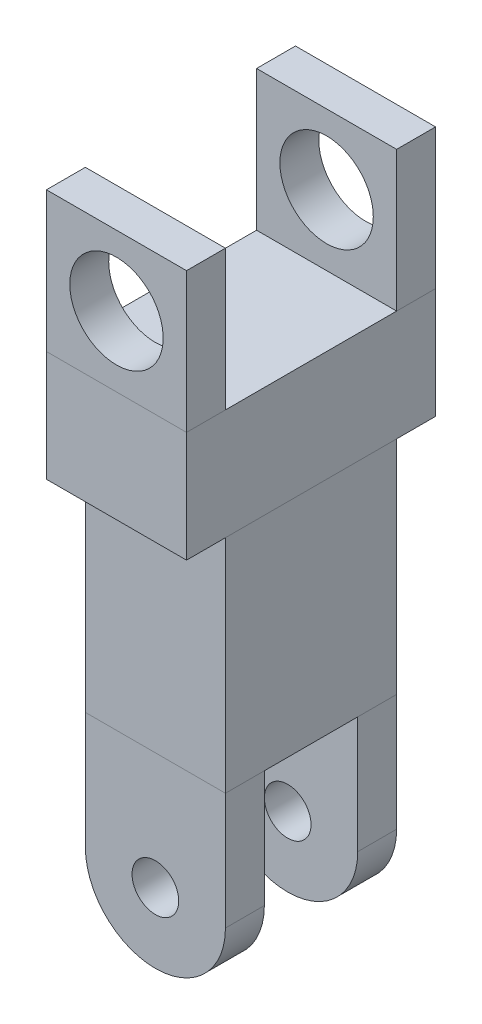
SolidWorks part; units mm, degrees
ref_plane "Front Plane" through (0, 0, 0) normal (0, 0, 1) x (1, 0, 0)
ref_plane "Top Plane" through (0, 0, 0) normal (0, 1, 0) x (1, 0, 0)
ref_plane "Right Plane" through (0, 0, 0) normal (1, 0, 0) x (0, 0, -1)
sketch "Sketch1" plane through (0, 0, 0) normal (0, 0, 1) x (1, 0, 0)
  line L0 (-4.5, 0) -> (-4.5, 7.5)
  line L5 (4.5, 0) -> (4.5, 7.5)
  line L6 (-4.5, 7.5) -> (4.5, 7.5)
  circle A0 centre (0, 0) radius 1.5
  circle A1 centre (0, 0) radius 4.5
  point P0 (0, 0)
  dimension "D3" = 3
  dimension "D4" = 9
  dimension "D1" = 7.5
  dimension "D2" = 7.5
extrude "Boss-Extrude1" add sketch "Sketch1" against normal blind 2.5 contours A1 A0 | A1 L5 L6 L0
sketch3d "3DSketch1"
  line L0 (0, 0, 0) -> (0, 0, -11)
  line L1 (0, 0, -11) -> (4.5, 0, -11)
  line L3 (0, 0, -11) -> (-4.5, 0, -11)
  dimension "D1" = 11
ref_plane "Plane1" through (0, 0, -11) normal (0, 0, -1) x (-1, 0, 0)
sketch "Sketch4" plane through (0, 0, -11) normal (0, 0, -1) x (-1, 0, 0)
  line L0 (-4.5, 0) -> (-4.5, 7.5)
  line L1 (4.5, 0) -> (4.5, 7.5)
  line L2 (-4.5, 7.5) -> (4.5, 7.5)
  circle A0 centre (0, 0) radius 4.5
  circle A1 centre (0, 0) radius 1.5
  dimension "D1" = 9
  dimension "D4" = 3
  dimension "D2" = 7.5
  dimension "D3" = 7.5
extrude "Boss-Extrude2" add sketch "Sketch4" against normal blind 2.5 separate body contours A0 A1 | A0 L1 L2 L0
sketch "Sketch5" plane through (0, 7.5, 0) normal (0, 1, 0) x (1, 0, 0)
  line L1 (4.5, 11) -> (-4.5, 11)
  line L2 (4.5, 11) -> (4.5, 0)
  line L3 (4.5, 0) -> (-4.5, 0)
  line L8 (-4.5, 11) -> (-4.5, 0)
extrude "Boss-Extrude3" add sketch "Sketch5" along normal blind 14.22 separate body
sketch "Sketch6" plane through (0, 21.72, 0) normal (0, 1, 0) x (1, 0, 0)
  line L0 (-4.5, 11) -> (-4.5, 13.5)
  line L1 (4.5, 0) -> (4.5, -2.5)
  line L3 (-4.5, 13.5) -> (4.5, 13.5)
  line L4 (-4.5, 13.5) -> (-4.5, -2.5)
  line L5 (-4.5, -2.5) -> (4.5, -2.5)
  line L6 (4.5, 13.5) -> (4.5, -2.5)
  line M3 (4.5, 0) -> (4.5, 11)
  line M4 (4.5, 11) -> (-4.5, 11)
  line M5 (-4.5, 11) -> (-4.5, 0)
  line M6 (-4.5, 0) -> (4.5, 0)
  dimension "D1" = 2.5
  dimension "D2" = 2.5
extrude "Boss-Extrude4" add sketch "Sketch6" along normal blind 7.11 separate body contours L6 L3 L0 M4 | M6 M3 M4 M5 | L4 L5 L1 M6
sketch "Sketch7" plane through (0, 28.83, 0) normal (0, 1, 0) x (1, 0, 0)
  line L0 (4.5, 13.5) -> (4.5, 11)
  line L1 (4.5, 13.5) -> (4.5, -2.5) construction
  line L2 (-4.5, -2.5) -> (-4.5, 13.5) construction
  line L3 (4.5, 13.5) -> (-4.5, 13.5)
  line L4 (4.5, 13.5) -> (4.5, 11)
  line L5 (4.5, 11) -> (-4.5, 11)
  line L6 (-4.5, 13.5) -> (-4.5, 11)
  line L7 (4.5, -2.5) -> (4.5, 0)
  line L9 (4.5, -2.5) -> (-4.5, -2.5)
  line L10 (4.5, -2.5) -> (4.5, 0)
  line L11 (4.5, 0) -> (-4.5, 0)
  line L12 (-4.5, -2.5) -> (-4.5, 0)
  line M6 (4.5, -2.5) -> (4.5, 13.5)
  line M7 (4.5, 13.5) -> (-4.5, 13.5)
  line M8 (-4.5, 13.5) -> (-4.5, -2.5)
  line M9 (-4.5, -2.5) -> (4.5, -2.5)
  dimension "D1" = 2.5
  dimension "D2" = 2.5
extrude "Boss-Extrude5" add sketch "Sketch7" along normal blind 9 separate body contours L5 M6 M7 M8 | L11 M6 M8 M9
sketch "Sketch8" plane through (0, 0, -13.5) normal (0, 0, -1) x (-1, 0, 0)
  line L0 (-4.5, 33.33) -> (0, 33.33)
  line L1 (-4.5, 37.83) -> (-4.5, 28.83) construction
  circle A0 centre (0, 33.33) radius 3
  dimension "D1" = 6
extrude "Cut-Extrude1" cut sketch "Sketch8" against normal blind 16 contours A0
